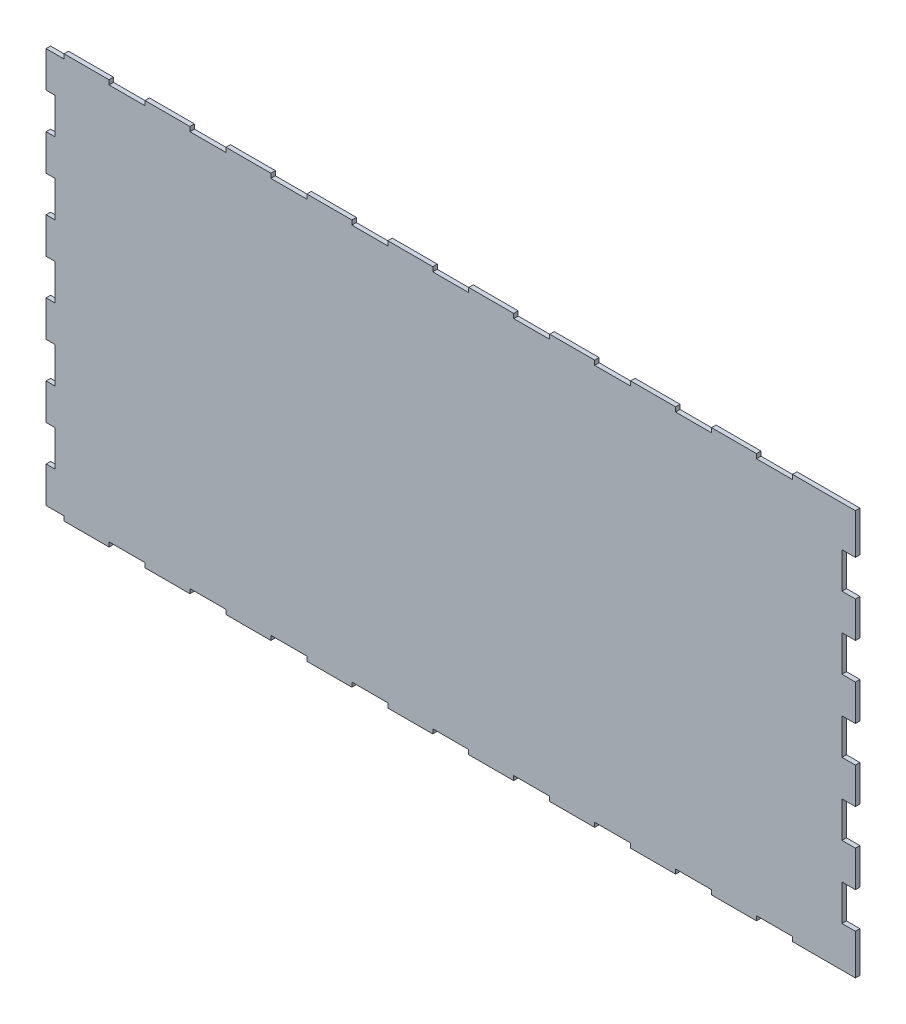
SolidWorks part; units mm, degrees
ref_plane "Front Plane" through (0, 0, 0) normal (0, 0, 1) x (1, 0, 0)
ref_plane "Top Plane" through (0, 0, 0) normal (0, 1, 0) x (1, 0, 0)
ref_plane "Right Plane" through (0, 0, 0) normal (1, 0, 0) x (0, 0, -1)
sketch "Sketch1" plane through (0, 0, 0) normal (0, 0, 1) x (1, 0, 0)
  line L0 (885, 100) -> (885, 60)
  line L1 (-900, 225) -> (-830, 225)
  line L2 (-900, 225) -> (-900, 180)
  line L4 (900, 225) -> (900, 180)
  line L5 (-900, 225) -> (900, -225) construction
  line L6 (-900, -225) -> (900, 225) construction
  line L7 (900, 180) -> (885, 180)
  line L9 (900, 140) -> (885, 140)
  line L10 (885, 180) -> (885, 140)
  line L11 (900, 100) -> (885, 100)
  line L12 (900, 60) -> (885, 60)
  line L13 (885, 20) -> (885, -20)
  line L14 (900, 20) -> (885, 20)
  line L15 (900, -20) -> (885, -20)
  line L16 (885, -60) -> (885, -100)
  line L17 (900, -60) -> (885, -60)
  line L18 (900, -100) -> (885, -100)
  line L19 (885, -140) -> (885, -180)
  line L20 (900, -140) -> (885, -140)
  line L21 (900, -180) -> (885, -180)
  line L22 (900, 60) -> (900, 20)
  line L23 (900, -20) -> (900, -60)
  line L24 (900, -100) -> (900, -140)
  line L25 (900, -180) -> (900, -225)
  line L26 (900, 140) -> (900, 100)
  line L27 (0, -1000) -> (0, -180) construction
  line L28 (-900, -180) -> (-885, -180)
  line L29 (-900, -140) -> (-885, -140)
  line L30 (-885, -140) -> (-885, -180)
  line L31 (-900, -100) -> (-885, -100)
  line L32 (-900, -60) -> (-885, -60)
  line L33 (-885, -60) -> (-885, -100)
  line L34 (-900, -20) -> (-885, -20)
  line L35 (-900, 20) -> (-885, 20)
  line L36 (-885, 20) -> (-885, -20)
  line L37 (-900, 60) -> (-885, 60)
  line L38 (-900, 100) -> (-885, 100)
  line L39 (-885, 180) -> (-885, 140)
  line L40 (-900, 140) -> (-885, 140)
  line L41 (-900, 180) -> (-885, 180)
  line L42 (-885, 100) -> (-885, 60)
  line L43 (-900, 140) -> (-900, 100)
  line L44 (-900, 60) -> (-900, 20)
  line L45 (-900, -20) -> (-900, -60)
  line L46 (-900, -100) -> (-900, -140)
  line L47 (-900, -180) -> (-900, -225)
  line L48 (-790, -225) -> (-740, -225)
  line L49 (790, 225) -> (790, 220) construction
  line L50 (790, 220) -> (830, 220) construction
  line L51 (830, 220) -> (830, 225) construction
  line L52 (-700, -225) -> (-650, -225)
  line L53 (700, 225) -> (700, 220) construction
  line L54 (700, 220) -> (740, 220) construction
  line L55 (740, 220) -> (740, 225) construction
  line L56 (-610, -225) -> (-560, -225)
  line L57 (610, 225) -> (610, 220) construction
  line L58 (610, 220) -> (650, 220) construction
  line L59 (650, 220) -> (650, 225) construction
  line L60 (-520, -225) -> (-470, -225)
  line L61 (520, 225) -> (520, 220) construction
  line L62 (520, 220) -> (560, 220) construction
  line L63 (560, 220) -> (560, 225) construction
  line L64 (-430, -225) -> (-380, -225)
  line L65 (430, 225) -> (430, 220) construction
  line L66 (430, 220) -> (470, 220) construction
  line L67 (470, 220) -> (470, 225) construction
  line L68 (-340, -225) -> (-290, -225)
  line L69 (340, 225) -> (340, 220) construction
  line L70 (340, 220) -> (380, 220) construction
  line L71 (380, 220) -> (380, 225) construction
  line L72 (-250, -225) -> (-200, -225)
  line L73 (250, 225) -> (250, 220) construction
  line L74 (250, 220) -> (290, 220) construction
  line L75 (290, 220) -> (290, 225) construction
  line L76 (-160, -225) -> (-110, -225)
  line L77 (160, 225) -> (160, 220) construction
  line L78 (160, 220) -> (200, 220) construction
  line L79 (200, 220) -> (200, 225) construction
  line L80 (-70, -225) -> (-20, -225)
  line L81 (70, 225) -> (70, 220) construction
  line L82 (70, 220) -> (110, 220) construction
  line L83 (110, 220) -> (110, 225) construction
  line L84 (20, -225) -> (70, -225)
  line L85 (-20, 225) -> (-20, 220) construction
  line L86 (-20, 220) -> (20, 220) construction
  line L87 (20, 220) -> (20, 225) construction
  line L88 (110, -225) -> (160, -225)
  line L89 (-110, 225) -> (-110, 220) construction
  line L90 (-110, 220) -> (-70, 220) construction
  line L91 (-70, 220) -> (-70, 225) construction
  line L92 (200, -225) -> (250, -225)
  line L93 (-200, 225) -> (-200, 220) construction
  line L94 (-200, 220) -> (-160, 220) construction
  line L95 (-160, 220) -> (-160, 225) construction
  line L96 (290, -225) -> (340, -225)
  line L97 (-290, 225) -> (-290, 220) construction
  line L98 (-290, 220) -> (-250, 220) construction
  line L99 (-250, 220) -> (-250, 225) construction
  line L100 (380, -225) -> (430, -225)
  line L101 (-380, 225) -> (-380, 220) construction
  line L102 (-380, 220) -> (-340, 220) construction
  line L103 (-340, 220) -> (-340, 225) construction
  line L104 (470, -225) -> (520, -225)
  line L105 (-470, 225) -> (-470, 220) construction
  line L106 (-470, 220) -> (-430, 220) construction
  line L107 (-430, 220) -> (-430, 225) construction
  line L108 (560, -225) -> (610, -225)
  line L109 (-560, 225) -> (-560, 220) construction
  line L110 (-560, 220) -> (-520, 220) construction
  line L111 (-520, 220) -> (-520, 225) construction
  line L112 (650, -225) -> (700, -225)
  line L113 (-650, 225) -> (-650, 220) construction
  line L114 (-650, 220) -> (-610, 220) construction
  line L115 (-610, 220) -> (-610, 225) construction
  line L116 (740, -225) -> (790, -225)
  line L117 (-740, 225) -> (-740, 220) construction
  line L118 (-740, 220) -> (-700, 220) construction
  line L119 (-700, 220) -> (-700, 225) construction
  line L120 (830, -225) -> (900, -225)
  line L121 (-830, 225) -> (-830, 220) construction
  line L122 (-830, 220) -> (-790, 220) construction
  line L123 (-790, 220) -> (-790, 225) construction
  line L125 (790, 225) -> (790, 220)
  line L126 (790, 220) -> (830, 220)
  line L127 (830, 220) -> (830, 225)
  line L129 (700, 225) -> (700, 220)
  line L130 (700, 220) -> (740, 220)
  line L131 (740, 220) -> (740, 225)
  line L133 (610, 225) -> (610, 220)
  line L134 (610, 220) -> (650, 220)
  line L135 (650, 220) -> (650, 225)
  line L137 (520, 225) -> (520, 220)
  line L138 (520, 220) -> (560, 220)
  line L139 (560, 220) -> (560, 225)
  line L141 (430, 225) -> (430, 220)
  line L142 (430, 220) -> (470, 220)
  line L143 (470, 220) -> (470, 225)
  line L145 (340, 225) -> (340, 220)
  line L146 (340, 220) -> (380, 220)
  line L147 (380, 220) -> (380, 225)
  line L149 (250, 225) -> (250, 220)
  line L150 (250, 220) -> (290, 220)
  line L151 (290, 220) -> (290, 225)
  line L153 (160, 225) -> (160, 220)
  line L154 (160, 220) -> (200, 220)
  line L155 (200, 220) -> (200, 225)
  line L157 (70, 225) -> (70, 220)
  line L158 (70, 220) -> (110, 220)
  line L159 (110, 220) -> (110, 225)
  line L161 (-20, 225) -> (-20, 220)
  line L162 (-20, 220) -> (20, 220)
  line L163 (20, 220) -> (20, 225)
  line L165 (-110, 225) -> (-110, 220)
  line L166 (-110, 220) -> (-70, 220)
  line L167 (-70, 220) -> (-70, 225)
  line L169 (-200, 225) -> (-200, 220)
  line L170 (-200, 220) -> (-160, 220)
  line L171 (-160, 220) -> (-160, 225)
  line L173 (-290, 225) -> (-290, 220)
  line L174 (-290, 220) -> (-250, 220)
  line L175 (-250, 220) -> (-250, 225)
  line L177 (-380, 225) -> (-380, 220)
  line L178 (-380, 220) -> (-340, 220)
  line L179 (-340, 220) -> (-340, 225)
  line L181 (-470, 225) -> (-470, 220)
  line L182 (-470, 220) -> (-430, 220)
  line L183 (-430, 220) -> (-430, 225)
  line L185 (-560, 225) -> (-560, 220)
  line L186 (-560, 220) -> (-520, 220)
  line L187 (-520, 220) -> (-520, 225)
  line L189 (-650, 225) -> (-650, 220)
  line L190 (-650, 220) -> (-610, 220)
  line L191 (-610, 220) -> (-610, 225)
  line L193 (-740, 225) -> (-740, 220)
  line L194 (-740, 220) -> (-700, 220)
  line L195 (-700, 220) -> (-700, 225)
  line L197 (-830, 225) -> (-830, 220)
  line L198 (-830, 220) -> (-790, 220)
  line L199 (-790, 220) -> (-790, 225)
  line L200 (830, 225) -> (900, 225)
  line L201 (740, 225) -> (790, 225)
  line L202 (650, 225) -> (700, 225)
  line L203 (560, 225) -> (610, 225)
  line L204 (470, 225) -> (520, 225)
  line L205 (380, 225) -> (430, 225)
  line L206 (290, 225) -> (340, 225)
  line L207 (200, 225) -> (250, 225)
  line L208 (110, 225) -> (160, 225)
  line L209 (20, 225) -> (70, 225)
  line L210 (-70, 225) -> (-20, 225)
  line L211 (-160, 225) -> (-110, 225)
  line L212 (-250, 225) -> (-200, 225)
  line L213 (-340, 225) -> (-290, 225)
  line L214 (-430, 225) -> (-380, 225)
  line L215 (-520, 225) -> (-470, 225)
  line L216 (-610, 225) -> (-560, 225)
  line L217 (-700, 225) -> (-650, 225)
  line L218 (-790, 225) -> (-740, 225)
  line L219 (0, 0) -> (226.4615, 0) construction
  line L220 (-740, -225) -> (-740, -220)
  line L222 (-830, -225) -> (-830, -220)
  line L223 (-830, -220) -> (-790, -220)
  line L224 (-790, -225) -> (-790, -220)
  line L225 (-700, -225) -> (-700, -220)
  line L226 (-740, -220) -> (-700, -220)
  line L227 (-650, -225) -> (-650, -220)
  line L228 (-610, -225) -> (-610, -220)
  line L229 (-650, -220) -> (-610, -220)
  line L230 (-560, -225) -> (-560, -220)
  line L231 (-520, -225) -> (-520, -220)
  line L232 (-560, -220) -> (-520, -220)
  line L233 (-470, -225) -> (-470, -220)
  line L234 (-430, -225) -> (-430, -220)
  line L235 (-470, -220) -> (-430, -220)
  line L236 (-380, -225) -> (-380, -220)
  line L237 (-340, -225) -> (-340, -220)
  line L238 (-380, -220) -> (-340, -220)
  line L239 (-290, -225) -> (-290, -220)
  line L240 (-250, -225) -> (-250, -220)
  line L241 (-290, -220) -> (-250, -220)
  line L242 (-200, -225) -> (-200, -220)
  line L243 (-160, -225) -> (-160, -220)
  line L244 (-200, -220) -> (-160, -220)
  line L245 (-110, -225) -> (-110, -220)
  line L246 (-70, -225) -> (-70, -220)
  line L247 (-110, -220) -> (-70, -220)
  line L248 (-20, -225) -> (-20, -220)
  line L249 (20, -225) -> (20, -220)
  line L250 (-20, -220) -> (20, -220)
  line L251 (70, -225) -> (70, -220)
  line L252 (110, -225) -> (110, -220)
  line L253 (70, -220) -> (110, -220)
  line L254 (160, -225) -> (160, -220)
  line L255 (200, -225) -> (200, -220)
  line L256 (160, -220) -> (200, -220)
  line L257 (250, -225) -> (250, -220)
  line L258 (290, -225) -> (290, -220)
  line L259 (250, -220) -> (290, -220)
  line L260 (340, -225) -> (340, -220)
  line L261 (380, -225) -> (380, -220)
  line L262 (340, -220) -> (380, -220)
  line L263 (430, -225) -> (430, -220)
  line L264 (470, -225) -> (470, -220)
  line L265 (430, -220) -> (470, -220)
  line L266 (520, -225) -> (520, -220)
  line L267 (560, -225) -> (560, -220)
  line L268 (520, -220) -> (560, -220)
  line L269 (610, -225) -> (610, -220)
  line L270 (650, -225) -> (650, -220)
  line L271 (610, -220) -> (650, -220)
  line L272 (700, -225) -> (700, -220)
  line L273 (740, -225) -> (740, -220)
  line L274 (700, -220) -> (740, -220)
  line L275 (790, -225) -> (790, -220)
  line L276 (830, -225) -> (830, -220)
  line L277 (790, -220) -> (830, -220)
  line L278 (-900, -225) -> (-830, -225)
  line L279 (10, 100) -> (10, 60)
  line L280 (0, 180) -> (10, 180)
  line L282 (0, 140) -> (10, 140)
  line L283 (10, 180) -> (10, 140)
  line L284 (0, 100) -> (10, 100)
  line L285 (0, 60) -> (10, 60)
  line L287 (10, 20) -> (10, -20)
  line L288 (0, 20) -> (10, 20)
  line L289 (0, -20) -> (10, -20)
  line L291 (10, -60) -> (10, -100)
  line L292 (0, -60) -> (10, -60)
  line L293 (0, -100) -> (10, -100)
  line L295 (10, -140) -> (10, -180)
  line L296 (0, -140) -> (10, -140)
  line L297 (0, -180) -> (10, -180)
  line L299 (0, 220) -> (0, 180)
  line L300 (0, 140) -> (0, 100)
  line L301 (0, 180) -> (0, 1220) construction
  line L302 (0, 60) -> (0, 20)
  line L303 (0, 100) -> (0, 140) construction
  line L304 (0, -20) -> (0, -60)
  line L305 (0, 20) -> (0, 60) construction
  line L306 (0, -100) -> (0, -140)
  line L307 (0, -60) -> (0, -20) construction
  line L308 (0, -180) -> (0, -220)
  line L309 (0, -140) -> (0, -100) construction
  point P0 (0, 0)
  point P211 (10, 0)
  dimension "D1" = 40
  dimension "D2" = 70
  dimension "D3" = 15
  dimension "D4" = 40
  dimension "D5" = 40
  dimension "D7" = 19
  dimension "D8" = 10
  dimension "D6" = 5
  dimension "D9" = 5
extrude "Boss-Extrude1" add sketch "Sketch1" along normal blind 5 contours L297 L308 L250 L249 L84 L251 L253 L252 L88 L254 L256 L255 L92 L257 L259 L258 L96 L260 L262 L261 L100 L263 L265 L264 L104 L266 L268 L267 L108 L269 L271 L270 L112 L272 L274 L273 L116 L275 L277 L276 L120 L25 L21 L19 L20 L24 L18 L16 L17 L23 L15
